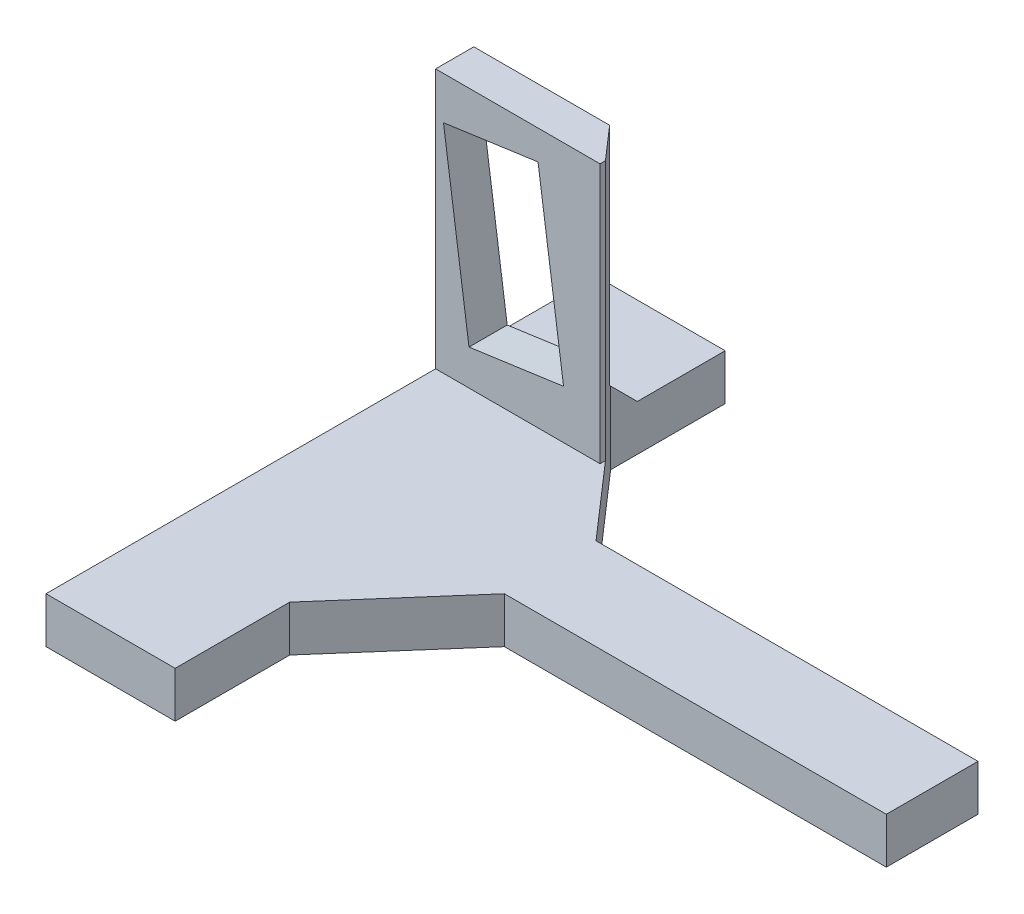
SolidWorks part; units mm, degrees
ref_plane "Front" through (0, 0, 0) normal (0, 0, 1) x (1, 0, 0)
ref_plane "Top" through (0, 0, 0) normal (0, 1, 0) x (1, 0, 0)
ref_plane "Right" through (0, 0, 0) normal (1, 0, 0) x (0, 0, -1)
sketch "Эскиз1" plane through (0, 0, 0) normal (0, 1, 0) x (1, 0, 0)
  line L0 (-49.8547, 33.0813) -> (-36.7609, 18.0813)
  line L1 (-36.7609, 18.0813) -> (13.2391, 18.0813)
  line L2 (-66.7609, 18.0813) -> (-66.7609, 6.0813)
  line L3 (-36.7609, 6.0813) -> (13.2391, 6.0813)
  line L4 (13.2391, 18.0813) -> (13.2391, 6.0813)
  line L5 (-66.7609, 48.0813) -> (-49.8547, 48.0813)
  line L6 (-66.7609, 48.0813) -> (-66.7609, 18.0813)
  line L8 (-49.8547, 48.0813) -> (-49.8547, 33.0813)
  line L10 (-66.7609, 6.0813) -> (-66.7609, -23.9187)
  line L11 (-66.7609, -23.9187) -> (-49.8547, -23.9187)
  line L12 (-49.8547, -8.9187) -> (-49.8547, -23.9187)
  line L13 (-49.8547, -8.9187) -> (-36.7609, 6.0813)
  line L14 (-36.7609, 18.0813) -> (-36.7609, 6.0813) construction
  dimension "D1" = 80
  dimension "D2" = 12
  dimension "D3" = 15
  dimension "D4" = 15
  dimension "D5" = 30
extrude "Бобышка-Вытянуть1" add sketch "Эскиз1" along normal blind 6
sketch "Эскиз2" plane through (0, 6, 0) normal (0, 1, 0) x (1, 0, 0)
  line L0 (13.2391, 12.0813) -> (-66.7609, 12.0813) construction
  line L1 (13.2391, 6.0813) -> (13.2391, 18.0813) construction
  line L2 (-66.7609, 48.0813) -> (-66.7609, -23.9187) construction
  line L3 (-36.7609, 18.0813) -> (-49.8547, 33.0813) construction
  line L4 (-66.7609, 32.0813) -> (-48.9818, 32.0813)
  line L5 (-66.7609, 32.0813) -> (-66.7609, 27.0813)
  line L6 (-66.7609, 27.0813) -> (-45.2334, 27.0813)
  line L7 (-45.2334, 27.7872) -> (-45.2334, 27.0813)
  line L8 (-45.2334, 27.7872) -> (-48.9818, 32.0813)
  dimension "D1" = 5
  dimension "D2" = 15
extrude "Бобышка-Вытянуть2" add sketch "Эскиз2" along normal blind 34
sketch "Эскиз3" plane through (0, 0, -32.0813) normal (0, 0, -1) x (-1, 0, 0)
  line L0 (51.6822, 24.2698) -> (64.0605, 22.5302) construction
  line L1 (53.3522, 36.153) -> (65.7306, 34.4134)
  line L2 (53.3522, 36.153) -> (50.0121, 12.3866)
  line L3 (50.0121, 12.3866) -> (62.3904, 10.647)
  line L4 (65.7306, 34.4134) -> (62.3904, 10.647)
  dimension "D1" = 24
  dimension "D2" = 12.5
extrude "Вырез-Вытянуть1" cut sketch "Эскиз3" against normal up to surface (5 mm away) up to face at (-55.9971, 23, -27.0813)
chamfer "Фаска1" distance 4.5 angle 45 1 edges at (-57.8713, 6, -32.0813)
